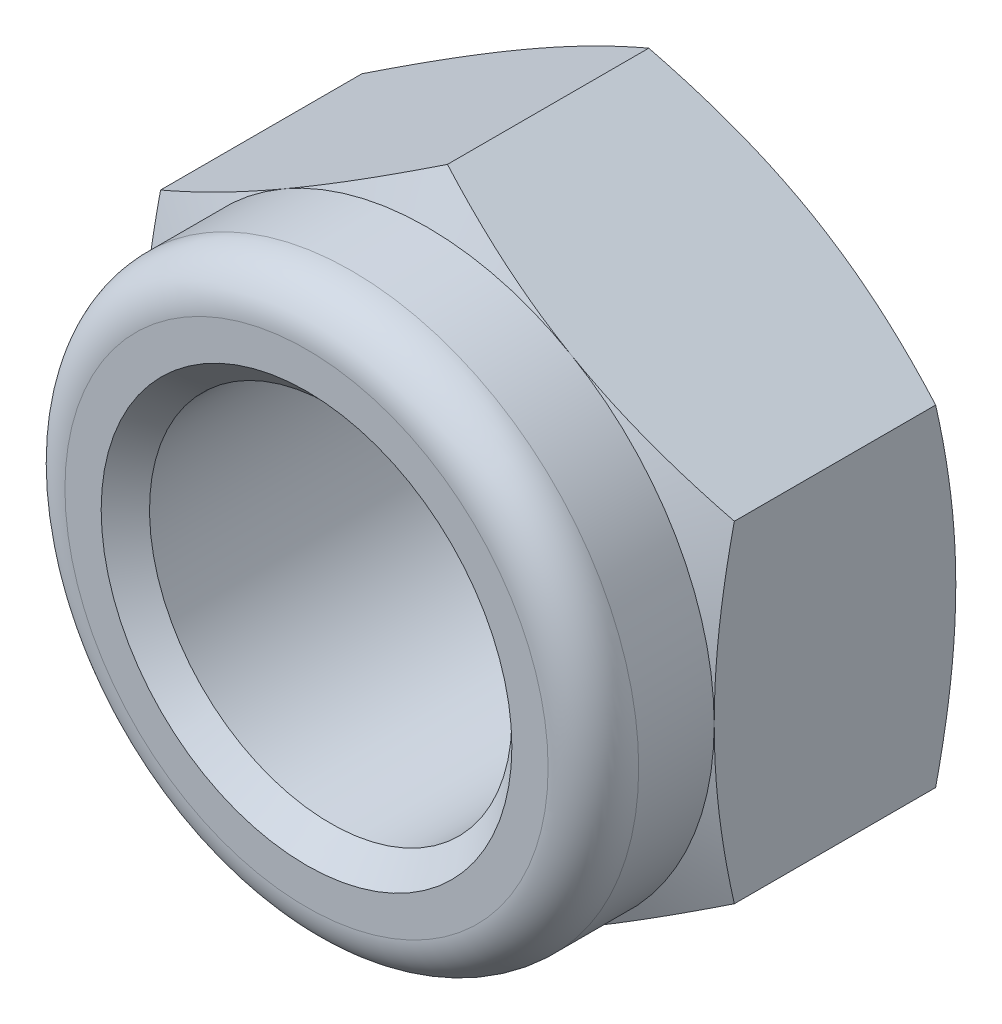
SolidWorks part; units mm, degrees
material "Plain Carbon Steel"
ref_plane "Front Plane" through (0, 0, 0) normal (0, 0, 1) x (1, 0, 0)
ref_plane "Top Plane" through (0, 0, 0) normal (0, 1, 0) x (1, 0, 0)
ref_plane "Right Plane" through (0, 0, 0) normal (1, 0, 0) x (0, 0, -1)
sketch "Sketch1" plane through (0, 0, 0) normal (0, 0, 1) x (1, 0, 0)
  line L1 (0, -10.9697) -> (9.5, -5.4848)
  line L2 (9.5, -5.4848) -> (9.5, 5.4848)
  line L3 (9.5, 5.4848) -> (0, 10.9697)
  line L4 (0, 10.9697) -> (-9.5, 5.4848)
  line L5 (-9.5, 5.4848) -> (-9.5, -5.4848)
  line L6 (-9.5, -5.4848) -> (0, -10.9697)
  circle A0 centre (0, 0) radius 9.5 construction
  circle A1 centre (0, 0) radius 6
  dimension "D2" = 12
  dimension "D1" = 19
extrude "Boss-Extrude1" add sketch "Sketch1" along normal blind 8
sketch "Sketch3" plane through (0, 0, 0) normal (0, 1, 0) x (0, 0, -1)
  line L0 (-8, 9.5) -> (-10.5, 9.5)
  line L1 (-8, -9.5) -> (-8, 0) construction
  line L2 (-12, 8) -> (-12, 6)
  line L3 (-12, 6) -> (-8, 6)
  line L5 (-8, 6) -> (-8, 9.5)
  line L6 (0, 0) -> (-2.4, 0) construction
  arc A0 (-10.5, 9.5) -> (-12, 8) centre (-10.5, 8) ccw
  dimension "D1" = 1.5
  dimension "D2" = 12
revolve "Revolve1" add sketch "Sketch3" angle 360 about L6
sketch "Sketch2" plane through (0, 0, 0) normal (1, 0, 0) x (0, 0, -1)
  line L0 (-8, 10.9697) -> (-8, 9.5)
  line L1 (-8, 5.4848) -> (-8, 8.2272) construction
  line L2 (-8, 9.5) -> (-7.3333, 10.9697)
  line L3 (-8, 10.9697) -> (0, 10.9697) construction
  line L4 (-7.3333, 10.9697) -> (-8, 10.9697)
  line L5 (-0.6667, 10.9697) -> (0, 10.9697)
  line L6 (0, 10.9697) -> (0, 9.5)
  line L7 (0, 5.4848) -> (0, 10.9697) construction
  line L8 (0, 9.5) -> (-0.6667, 10.9697)
  line L9 (-7.3333, 10.9697) -> (-6.6667, 10.9697) construction
  line L10 (-6.6667, 10.9697) -> (-6, 10.9697) construction
  line L11 (-6, 10.9697) -> (-5.3333, 10.9697) construction
  line L12 (-5.3333, 10.9697) -> (-4.6667, 10.9697) construction
  line L13 (-4.6667, 10.9697) -> (-4, 10.9697) construction
  line L14 (-4, 10.9697) -> (-3.3333, 10.9697) construction
  line L15 (-3.3333, 10.9697) -> (-2.6667, 10.9697) construction
  line L16 (-2.6667, 10.9697) -> (-2, 10.9697) construction
  line L17 (-2, 10.9697) -> (-1.3333, 10.9697) construction
  line L18 (0, 0) -> (-2.4, 0) construction
  line L20 (-12, 6) -> (-11.2, 6)
  line L21 (-11.2, 6) -> (-12, 6.8)
  line L22 (-12, 6.8) -> (-12, 6)
  line L23 (0, 6) -> (-0.8, 6)
  line L24 (0, -5.4848) -> (0, 5.4848) construction
  line L25 (-0.8, 6) -> (0, 6.8)
  line L26 (0, 6.8) -> (0, 6)
  line L27 (-12, 8) -> (-12, -8) construction
  line L28 (-6.4, 6) -> (-7.2, 6) construction
  line L29 (-7.2, 6) -> (-8, 6) construction
  line L30 (-6.4, 6) -> (-5.6, 6) construction
  line L31 (-5.6, 6) -> (-4.8, 6) construction
  line L32 (-4.8, 6) -> (-4, 6) construction
  line L33 (-4, 6) -> (-3.2, 6) construction
  line L34 (-3.2, 6) -> (-2.4, 6) construction
  line L35 (-2.4, 6) -> (-1.6, 6) construction
  line L36 (-1.6, 6) -> (-0.8, 6) construction
  line L37 (-1.3333, 10.9697) -> (-0.6667, 10.9697) construction
  line L38 (-8, 0) -> (-8, 5.4848) construction
  dimension "D1" = 19
revolve "Cut-Revolve1" cut sketch "Sketch2" angle 360 about L18
